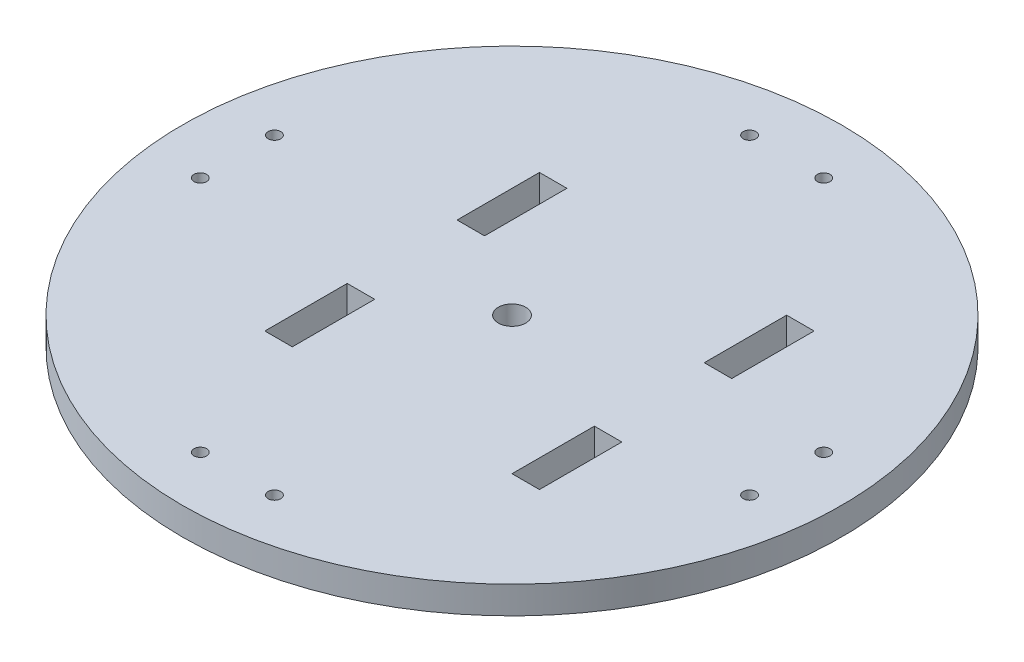
SolidWorks part; units mm, degrees
material "PVC Rigid"
ref_plane "Front Plane" through (0, 0, 0) normal (0, 0, 1) x (1, 0, 0)
ref_plane "Top Plane" through (0, 0, 0) normal (0, 1, 0) x (1, 0, 0)
ref_plane "Right Plane" through (0, 0, 0) normal (1, 0, 0) x (0, 0, -1)
sketch "Sketch1" plane through (0, 0, 0) normal (0, 1, 0) x (1, 0, 0)
  circle A0 centre (0, 0) radius 60
  circle A1 centre (0, 0) radius 2.5
  point P25 (0, 0)
  dimension "D1" = 120
  dimension "D5" = 5
extrude "Boss-Extrude1" add sketch "Sketch1" along normal blind 5
sketch "Sketch3" plane through (0, 5, 0) normal (0, 1, 0) x (1, 0, 0)
  line L0 (-60, 0) -> (60, 0)
  line L1 (0, 60) -> (0, -60)
  circle A0 centre (0, 0) radius 60 construction
sketch "Sketch4" plane through (0, 5, 0) normal (0, 1, 0) x (1, 0, 0)
  line L0 (-60, 0) -> (60, 0) construction
  line L1 (0, 60) -> (0, -60) construction
  circle A0 centre (-6.75, 50) radius 1.15
  circle A2 centre (50, 6.75) radius 1.15
  circle A4 centre (6.75, -50) radius 1.15
  circle A6 centre (-50, -6.75) radius 1.15
  circle A8 centre (6.75, 50) radius 1.15
  circle A9 centre (50, -6.75) radius 1.15
  circle A10 centre (-6.75, -50) radius 1.15
  circle A11 centre (-50, 6.75) radius 1.15
  point P23 (0, 0)
  point P25 (0, 0)
  dimension "D2" = 2.3
  dimension "D1" = 50
  dimension "D3" = 6.75
  dimension "D4" = 4
  dimension "D5" = 4
extrude "Cut-Extrude1" cut sketch "Sketch4" against normal blind 5
sketch "Sketch5" plane through (0, 5, 0) normal (0, 1, 0) x (1, 0, 0)
  line L0 (-60, 0) -> (60, 0) construction
  line L1 (-20, 25) -> (-15, 25)
  line L2 (-20, 25) -> (-20, 10)
  line L3 (-20, 10) -> (-15, 10)
  line L4 (-15, 25) -> (-15, 10)
  line L5 (-20, -10) -> (-15, -10)
  line L6 (-20, -10) -> (-20, -25)
  line L7 (-20, -25) -> (-15, -25)
  line L8 (-15, -10) -> (-15, -25)
  line L9 (0, 60) -> (0, -60) construction
  dimension "D1" = 5
  dimension "D2" = 5
  dimension "D3" = 20
  dimension "D4" = 10
  dimension "D5" = 15
  dimension "D6" = 15
  dimension "D7" = 15
  dimension "D8" = 15
extrude "Cut-Extrude2" cut sketch "Sketch5" against normal blind 5
sketch "Sketch6" plane through (0, 5, 0) normal (0, 1, 0) x (1, 0, 0)
  line L0 (-60, 0) -> (60, 0) construction
  line L1 (25, 25) -> (30, 25)
  line L2 (25, 25) -> (25, 10)
  line L3 (25, 10) -> (30, 10)
  line L4 (30, 25) -> (30, 10)
  line L5 (25, -10) -> (30, -10)
  line L6 (25, -10) -> (25, -25)
  line L7 (25, -25) -> (30, -25)
  line L8 (30, -10) -> (30, -25)
  line L9 (0, 60) -> (0, -60) construction
  dimension "D1" = 15
  dimension "D2" = 15
  dimension "D3" = 5
  dimension "D4" = 5
  dimension "D5" = 10
  dimension "D6" = 20
  dimension "D7" = 25
  dimension "D8" = 25
extrude "Cut-Extrude3" cut sketch "Sketch6" against normal blind 5
